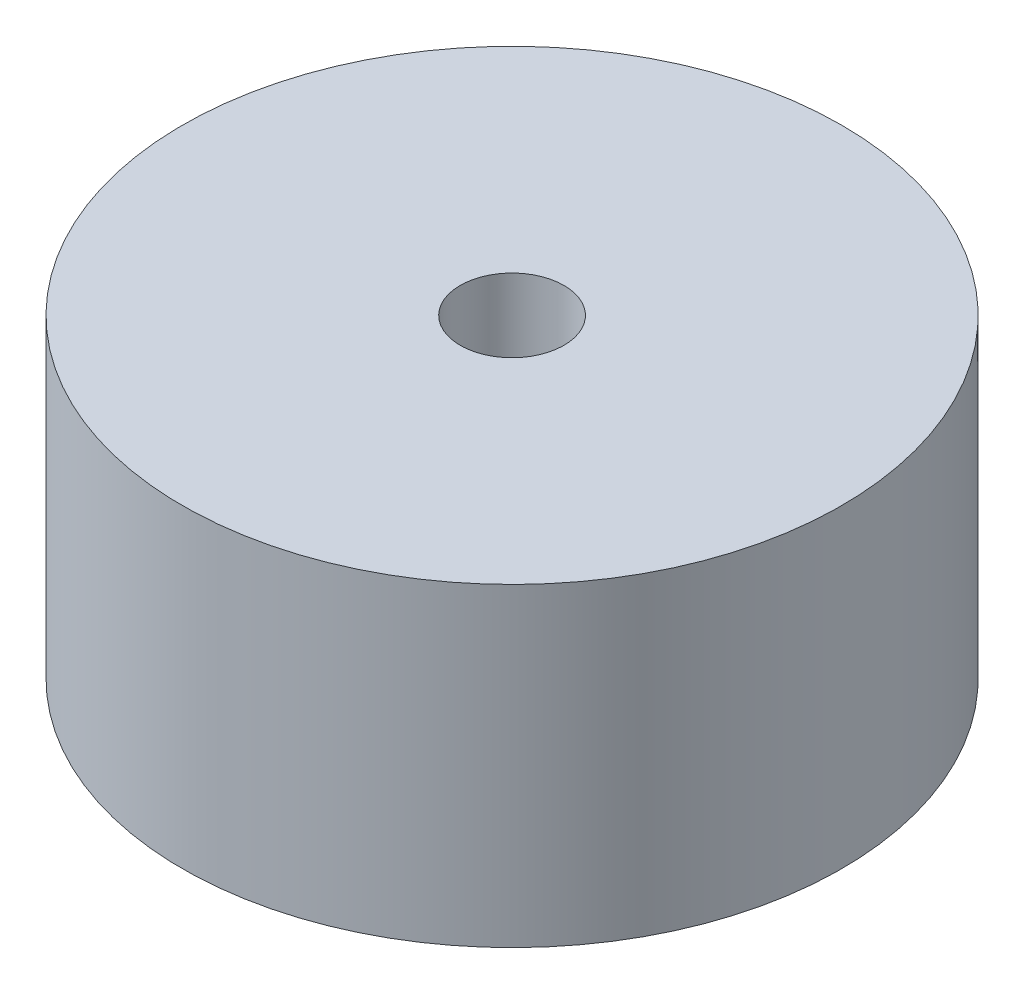
SolidWorks part; units mm, degrees
ref_plane "Front Plane" through (0, 0, 0) normal (0, 0, 1) x (1, 0, 0)
ref_plane "Top Plane" through (0, 0, 0) normal (0, 1, 0) x (1, 0, 0)
ref_plane "Right Plane" through (0, 0, 0) normal (1, 0, 0) x (0, 0, -1)
sketch "Sketch1" plane through (0, 0, 0) normal (0, 1, 0) x (1, 0, 0)
  circle A0 centre (0, 0) radius 31.75
  dimension "D1" = 63.5
extrude "Boss-Extrude1" add sketch "Sketch1" along normal blind 30.3
sketch "Sketch2" plane through (0, 0, 0) normal (0, -1, 0) x (1, 0, 0)
  circle A0 centre (0, 0) radius 5
  dimension "D1" = 10
extrude "Cut-Extrude1" cut sketch "Sketch2" against normal through all
sketch "Sketch3" plane through (0, 0, 0) normal (0, 0, 1) x (1, 0, 0)
  line L0 (0, 0) -> (0, 30.3) construction
  line L1 (31.75, 30.3) -> (-31.75, 30.3) construction
  line L2 (-3.0236, 15.15) -> (2.3258, 15.15) construction
ref_point "Point1"
